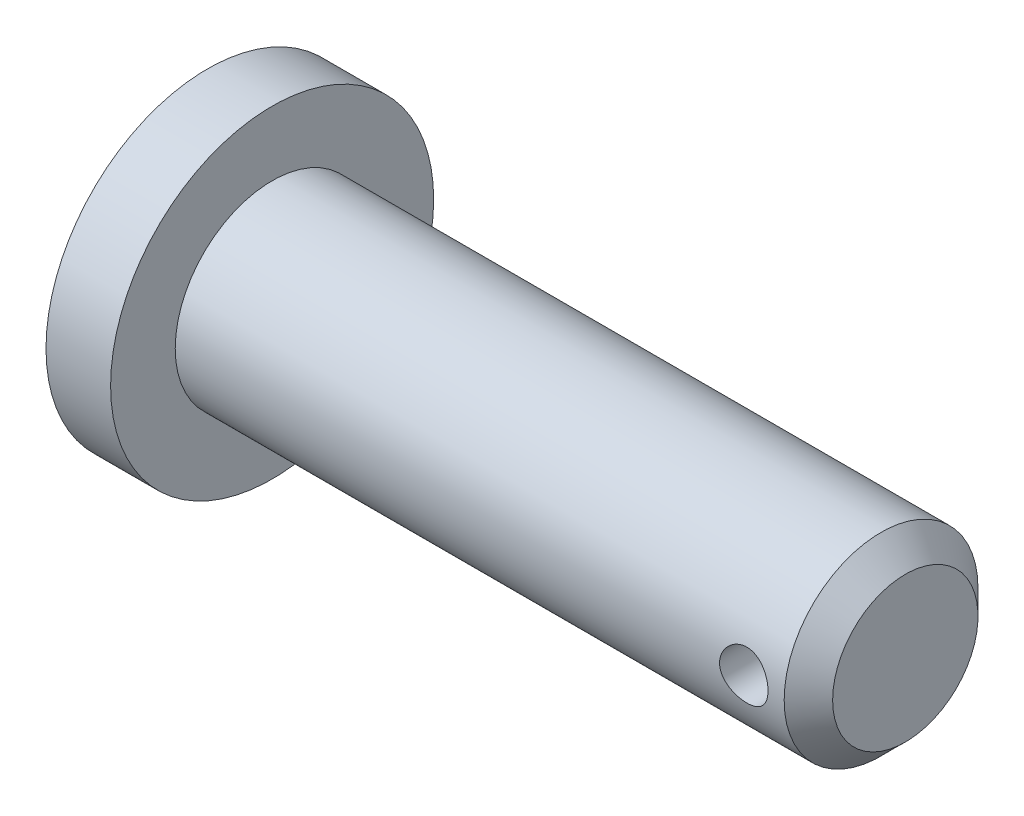
SolidWorks part; units mm, degrees
material "AISI 1035 Steel (SS)"
ref_plane "Front Plane" through (0, 0, 0) normal (0, 0, 1) x (1, 0, 0)
ref_plane "Top Plane" through (0, 0, 0) normal (0, 1, 0) x (1, 0, 0)
ref_plane "Right Plane" through (0, 0, 0) normal (1, 0, 0) x (0, 0, -1)
sketch "Sketch1" plane through (0, 0, 0) normal (0, 0, 1) x (1, 0, 0)
  line L0 (-34.29, 0) -> (34.29, 0) construction
  line L1 (-34.29, 0) -> (-34.29, 15.875)
  line L2 (-34.29, 15.875) -> (-27.94, 15.875)
  line L3 (-27.94, 15.875) -> (-27.94, 9.525)
  line L4 (-27.94, 9.525) -> (34.29, 9.525)
  line L5 (34.29, 9.525) -> (34.29, 0)
  line L6 (-34.29, 0) -> (34.29, 0)
  dimension "D1" = 68.58
  dimension "D2" = 31.75
  dimension "D3" = 19.05
  dimension "D4" = 6.35
revolve "Pin Body" add sketch "Sketch1" angle 360 about L0
sketch "Sketch2" plane through (0, 0, 0) normal (0, 0, 1) x (1, 0, 0)
  line L0 (-34.29, 0) -> (34.29, 0) construction
  line L1 (-34.29, 15.875) -> (-34.29, -15.875) construction
  line L2 (34.29, -9.525) -> (34.29, 9.525) construction
  circle A0 centre (27.94, 0) radius 2.3813
  dimension "D1" = 4.7625
  dimension "D2" = 62.23
extrude "Cut-Extrude1" cut sketch "Sketch2" against normal through all both and the other way through all
chamfer "Chamfer1" distance 2.3813 angle 45 1 edges at (34.29, 0, 9.525)
